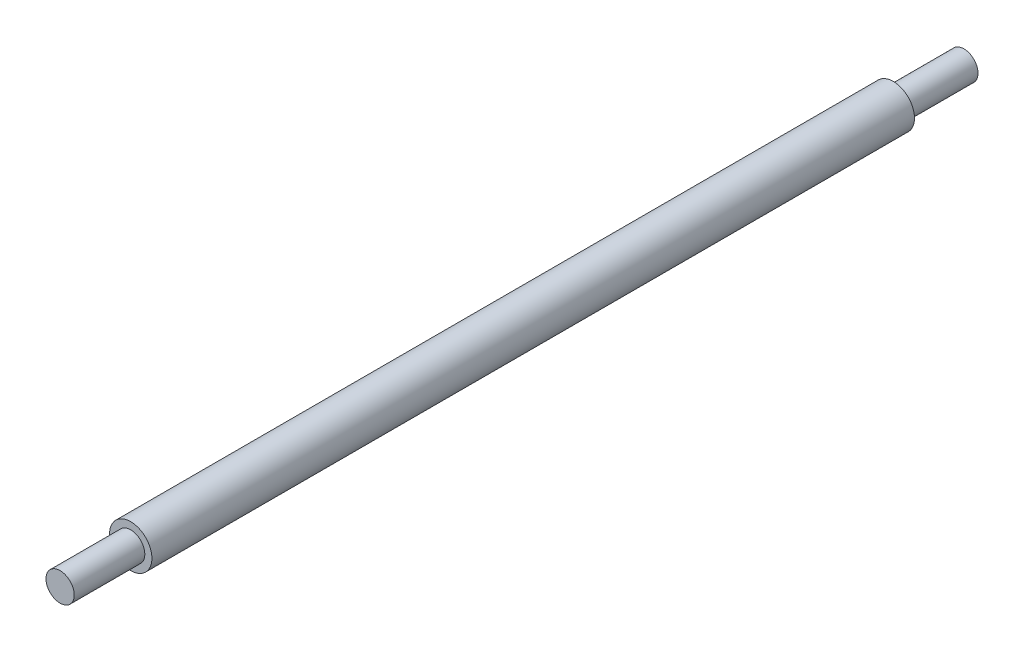
SolidWorks part; units mm, degrees
ref_plane "Front" through (0, 0, 0) normal (0, 0, 1) x (1, 0, 0)
ref_plane "Top" through (0, 0, 0) normal (0, 1, 0) x (1, 0, 0)
ref_plane "Right" through (0, 0, 0) normal (1, 0, 0) x (0, 0, -1)
sketch "Sketch1" plane through (0, 0, 0) normal (0, 0, 1) x (1, 0, 0)
  circle A0 centre (0, 0) radius 9.525
  dimension "D1" = 19.05
extrude "Boss-Extrude1" add sketch "Sketch1" along normal blind 342.9
sketch "Sketch2" plane through (0, 0, 342.9) normal (0, 0, 1) x (1, 0, 0)
  circle A0 centre (0, 0) radius 6.35
  dimension "D1" = 12.7
extrude "Boss-Extrude2" add sketch "Sketch2" along normal blind 31.75
sketch "Sketch3" plane through (0, 0, 0) normal (0, 0, -1) x (-1, 0, 0)
  circle A0 centre (0, 0) radius 6.35
  dimension "D1" = 12.7
extrude "Boss-Extrude3" add sketch "Sketch3" along normal blind 31.75
